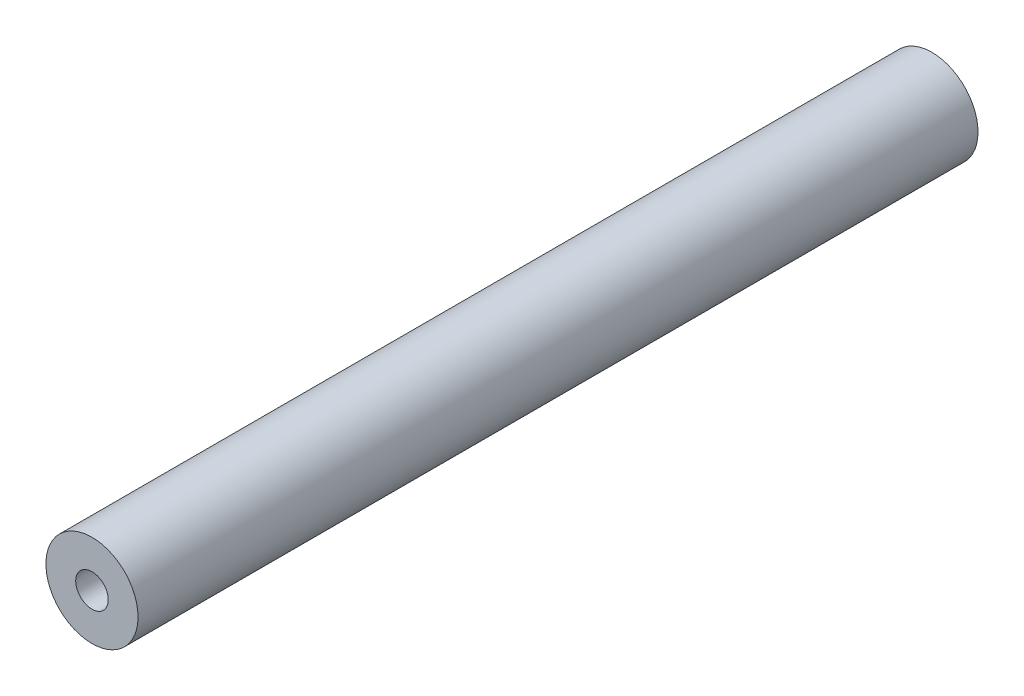
SolidWorks part; units mm, degrees
ref_plane "Спереди" through (0, 0, 0) normal (0, 0, 1) x (1, 0, 0)
ref_plane "Сверху" through (0, 0, 0) normal (0, 1, 0) x (1, 0, 0)
ref_plane "Справа" through (0, 0, 0) normal (1, 0, 0) x (0, 0, -1)
sketch "Эскиз1" plane through (0, 0, 0) normal (0, 0, 1) x (1, 0, 0)
  circle A0 centre (0, 0) radius 8.5
  circle A1 centre (0, 0) radius 3
extrude "Axle_envelope" add sketch "Эскиз1" along normal blind 155 from offset 75
